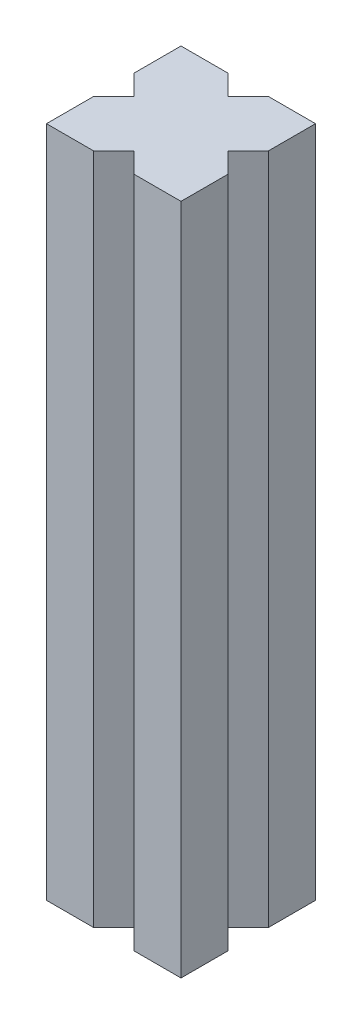
SolidWorks part; units mm, degrees
ref_plane "Front" through (0, 0, 0) normal (0, 0, 1) x (1, 0, 0)
ref_plane "Top" through (0, 0, 0) normal (0, 1, 0) x (1, 0, 0)
ref_plane "Right" through (0, 0, 0) normal (1, 0, 0) x (0, 0, -1)
sketch "Skizze1" plane through (0, 0, 0) normal (0, 1, 0) x (1, 0, 0)
  line L1 (0, 0) -> (20, 0)
  line L2 (0, 0) -> (0, 20)
  line L3 (0, 20) -> (20, 20)
  line L4 (20, 0) -> (20, 20)
  dimension "D1" = 20
extrude "Aufsatz-Linear austragen1" add sketch "Skizze1" along normal blind 100
sketch "Skizze2" plane through (0, 100, 0) normal (0, 1, 0) x (1, 0, 0)
  line L0 (10, 20) -> (10, 0) construction
  line L1 (0, 10) -> (20, 10) construction
  line L2 (7, 20) -> (10, 17)
  line L3 (13, 20) -> (10, 17)
  line L4 (10, 10) -> (20, 20) construction
  line L5 (7, 20) -> (13, 20)
  line L6 (20, 13) -> (17, 10)
  line L7 (20, 7) -> (17, 10)
  line L8 (20, 7) -> (20, 13)
  line L9 (0, 7) -> (0, 13)
  line L10 (0, 7) -> (3, 10)
  line L11 (0, 13) -> (3, 10)
  line L12 (7, 0) -> (13, 0)
  line L13 (13, 0) -> (10, 3)
  line L14 (7, 0) -> (10, 3)
  line L15 (20, 20) -> (0, 20) construction
  line L16 (20, 0) -> (20, 20) construction
  line L17 (0, 0) -> (20, 0) construction
  dimension "D1" = 3
  dimension "D2" = 3
extrude "Schnitt-Linear austragen1" cut sketch "Skizze2" against normal through all
